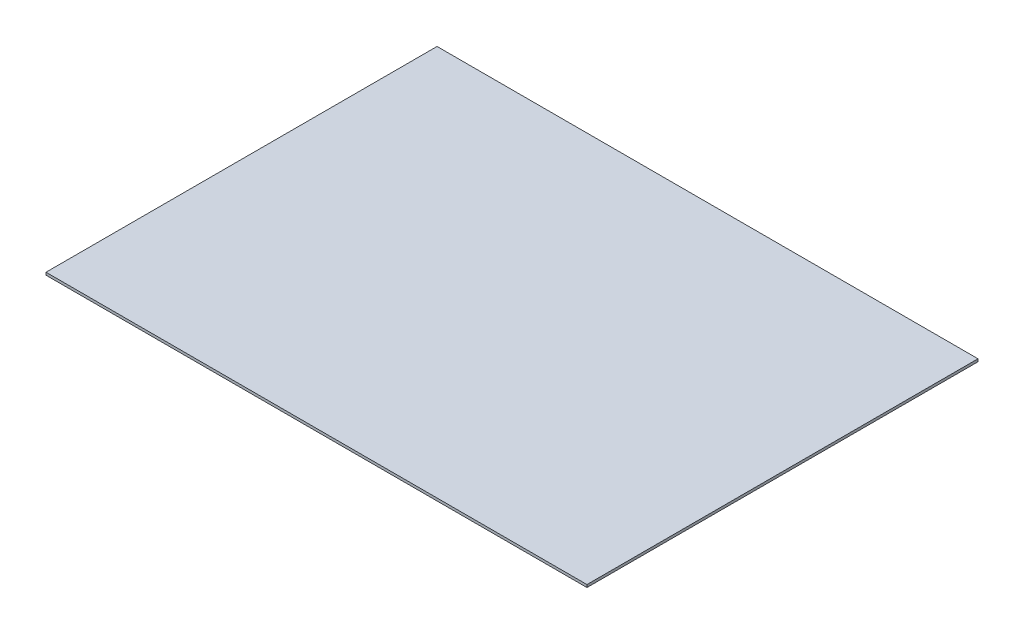
SolidWorks part; units mm, degrees
ref_plane "Front Plane" through (0, 0, 0) normal (0, 0, 1) x (1, 0, 0)
ref_plane "Top Plane" through (0, 0, 0) normal (0, 1, 0) x (1, 0, 0)
ref_plane "Right Plane" through (0, 0, 0) normal (1, 0, 0) x (0, 0, -1)
sketch "Sketch3" plane through (0, 0, 0) normal (0, 1, 0) x (1, 0, 0)
  line L1 (-205.0343, 135.8044) -> (209.9657, 135.8044)
  line L2 (-205.0343, 135.8044) -> (-205.0343, -164.1956)
  line L3 (-205.0343, -164.1956) -> (209.9657, -164.1956)
  line L4 (209.9657, 135.8044) -> (209.9657, -164.1956)
  line L5 (-205.0343, 135.8044) -> (209.9657, -164.1956) construction
  line L6 (-205.0343, -164.1956) -> (209.9657, 135.8044) construction
  point P0 (2.4657, -14.1956)
  dimension "D1" = 415
  dimension "D2" = 300
extrude "Boss-Extrude1" add sketch "Sketch3" along normal blind 2
sketch "Sketch4" plane through (0, 2, 0) normal (0, 1, 0) x (1, 0, 0)
  line L0 (-190.0343, 120.8044) -> (-190.0343, -149.1956)
  line L1 (-205.0343, 135.8044) -> (209.9657, 135.8044)
  line L2 (-205.0343, 135.8044) -> (-205.0343, -164.1956)
  line L3 (-205.0343, -164.1956) -> (209.9657, -164.1956)
  line L4 (209.9657, 135.8044) -> (209.9657, -164.1956)
  line L5 (-190.0343, -149.1956) -> (194.9657, -149.1956)
  line L6 (194.9657, 120.8044) -> (194.9657, -149.1956)
  line L7 (-190.0343, 120.8044) -> (194.9657, 120.8044)
  line L8 (-185.0343, 115.8044) -> (-185.0343, -144.1956)
  line L9 (-190.0343, 120.8044) -> (194.9657, 120.8044)
  line L10 (-190.0343, 120.8044) -> (-190.0343, -149.1956)
  line L11 (-190.0343, -149.1956) -> (194.9657, -149.1956)
  line L12 (194.9657, 120.8044) -> (194.9657, -149.1956)
  line L13 (-185.0343, -144.1956) -> (189.9657, -144.1956)
  line L14 (189.9657, 115.8044) -> (189.9657, -144.1956)
  line L15 (-185.0343, 115.8044) -> (189.9657, 115.8044)
  dimension "D1" = 15
  dimension "D2" = 5
extrude "Boss-Extrude2" add sketch "Sketch4" against normal blind 10 contours L7 L0 L5 L6 L8 L15 L14 L13
